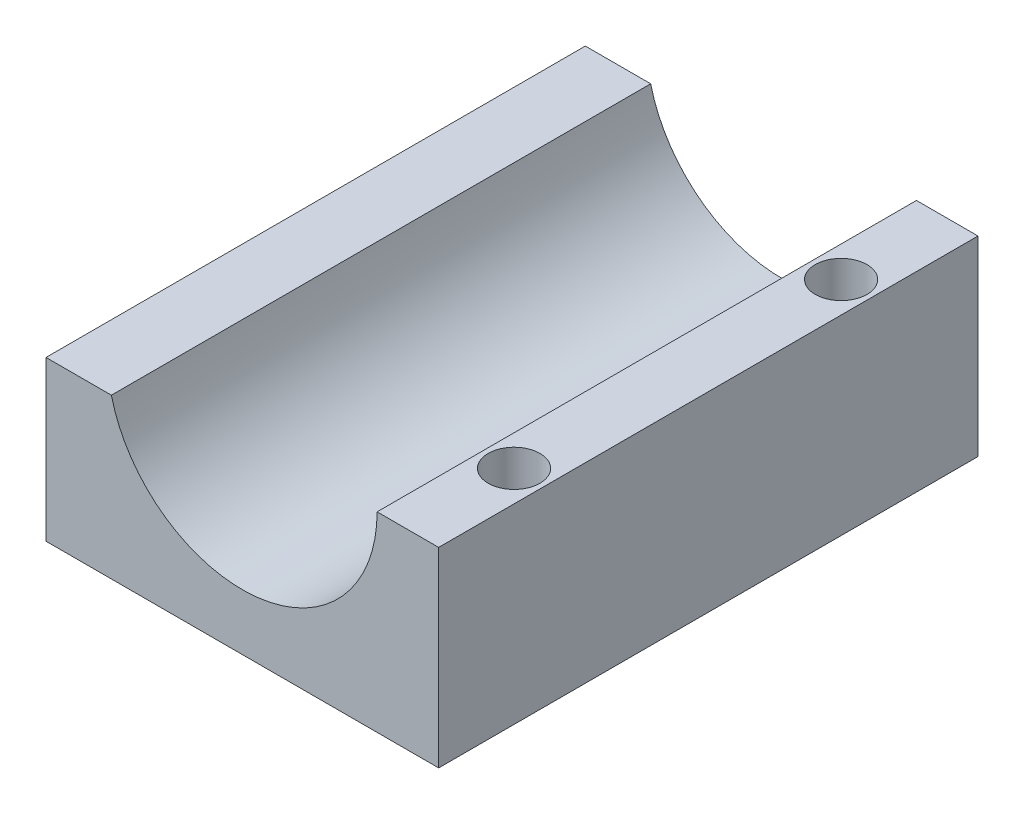
SolidWorks part; units mm, degrees
ref_plane "Front Plane" through (0, 0, 0) normal (0, 0, 1) x (1, 0, 0)
ref_plane "Top Plane" through (0, 0, 0) normal (0, 1, 0) x (1, 0, 0)
ref_plane "Right Plane" through (0, 0, 0) normal (1, 0, 0) x (0, 0, -1)
sketch "Sketch2" plane through (0, 0, 0) normal (0, 1, 0) x (1, 0, 0)
  line L1 (0, 0) -> (18.5, 0)
  line L2 (0, 0) -> (0, 25.41)
  line L3 (0, 25.41) -> (18.5, 25.41)
  line L4 (18.5, 0) -> (18.5, 25.41)
extrude "Boss-Extrude1" add sketch "Sketch2" along normal blind 9
sketch "Sketch6" plane through (0, 0, 0) normal (0, 0, 1) x (1, 0, 0)
  line L0 (0, 9) -> (18.5, 9) construction
  line L1 (2.9, 9) -> (15.6, 9)
  arc A0 (2.9, 9) -> (15.6, 9) centre (9.25, 9) ccw
extrude "Cut-Extrude1" cut sketch "Sketch6" against normal blind 25.41
sketch "Sketch7" plane through (0, 0, 0) normal (0, -1, 0) x (-1, 0, 0)
  line L0 (0, 0) -> (0, 5)
  line L1 (0, 25.41) -> (0, 0) construction
  line L2 (0, 5) -> (-18.5, 5)
  line L3 (-18.5, 0) -> (-18.5, 25.41) construction
  line L4 (0, 25.41) -> (0, 20.41)
  line L5 (0, 20.41) -> (-18.5, 20.41)
sketch "Sketch10" plane through (0, 9, 0) normal (0, 1, 0) x (1, 0, 0)
  line L0 (17.05, 25.41) -> (17.05, 20.41)
  line L1 (18.5, 25.41) -> (15.6, 25.41) construction
  line L2 (17.05, 0) -> (17.05, 5)
  line L3 (15.6, 0) -> (18.5, 0) construction
  circle A0 centre (17.05, 20.41) radius 1.22
  circle A1 centre (17.05, 5) radius 1.22
sketch "Sketch14" plane through (0, 0, -25.41) normal (0, 0, -1) x (-1, 0, 0)
  line L0 (0, 9) -> (0, 7.5)
  line L1 (0, 9) -> (0, 0) construction
  line L2 (0, 7.5) -> (-3.2467, 7.5)
  line L3 (-3.2467, 7.5) -> (-2.9, 9)
extrude "Cut-Extrude3" cut sketch "Sketch14" against normal blind 25.41 and the other way through all flip side to cut
extrude "Cut-Extrude4" cut sketch "Sketch10" against normal through all
